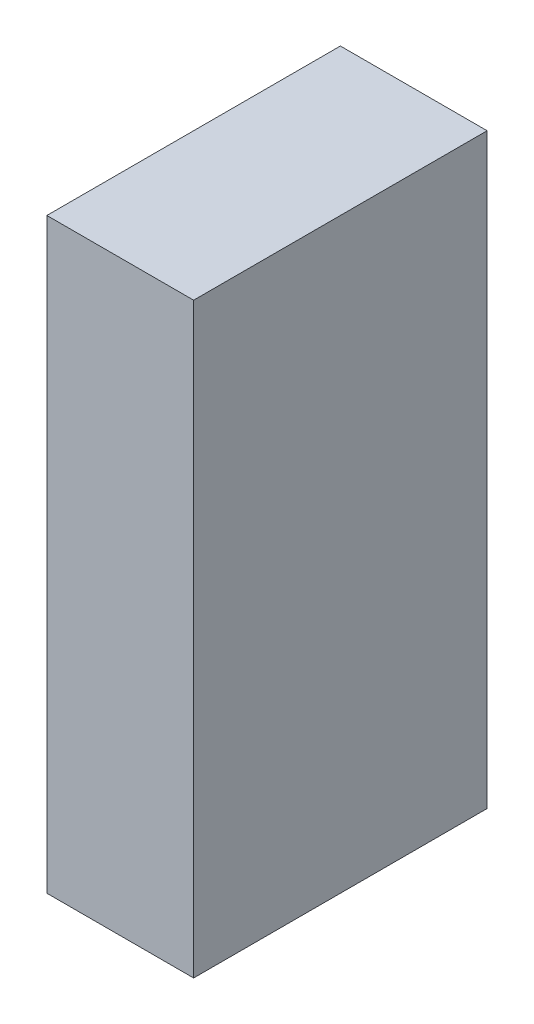
SolidWorks part; units mm, degrees
ref_plane "Front Plane" through (0, 0, 0) normal (0, 0, 1) x (1, 0, 0)
ref_plane "Top Plane" through (0, 0, 0) normal (0, 1, 0) x (1, 0, 0)
ref_plane "Right Plane" through (0, 0, 0) normal (1, 0, 0) x (0, 0, -1)
sketch "Sketch2" plane through (0, 0, 0) normal (0, 0, 1) x (1, 0, 0)
  line L3 (-12.7, 50.8) -> (12.7, 50.8)
  line L4 (-12.7, 50.8) -> (-12.7, -50.8)
  line L5 (-12.7, -50.8) -> (12.7, -50.8)
  line L6 (12.7, 50.8) -> (12.7, -50.8)
  point P4 (0, 0)
  point P8 (0, 0)
  dimension "D1" = 101.6
  dimension "D2" = 25.4
  dimension "D3" = 12.7
  dimension "D4" = 50.8
extrude "Boss-Extrude1" add sketch "Sketch2" along normal mid plane 50.8 contours L4 L5 L6 L3
